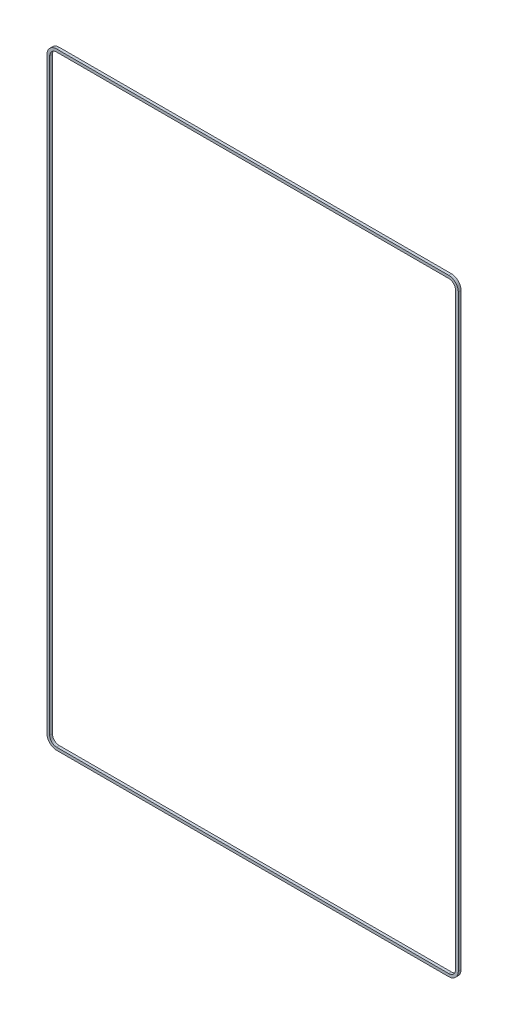
SolidWorks part; units mm, degrees
ref_plane "Front Plane" through (0, 0, 0) normal (0, 0, 1) x (1, 0, 0)
ref_plane "Top Plane" through (0, 0, 0) normal (0, 1, 0) x (1, 0, 0)
ref_plane "Right Plane" through (0, 0, 0) normal (1, 0, 0) x (0, 0, -1)
sketch "Sketch1" plane through (0, 0, 0) normal (0, 0, 1) x (1, 0, 0)
  line L0 (4.318, -2.032) -> (258.318, -2.032) construction
  line L1 (4.318, 0) -> (258.318, 0) construction
  line L2 (0, 4.318) -> (0, 385.318) construction
  line L3 (4.318, 389.636) -> (258.318, 389.636) construction
  line L4 (262.636, 4.318) -> (262.636, 385.318) construction
  line L5 (264.668, 4.318) -> (264.668, 385.318) construction
  line L6 (4.318, 391.668) -> (258.318, 391.668) construction
  line L7 (-2.032, 4.318) -> (-2.032, 385.318) construction
  line L8 (-0.127, 4.318) -> (-0.127, 385.318)
  line L9 (4.318, 389.763) -> (258.318, 389.763)
  line L10 (262.763, 4.318) -> (262.763, 385.318)
  line L11 (4.318, -0.127) -> (258.318, -0.127)
  line L12 (-1.905, 4.318) -> (-1.905, 385.318)
  line L13 (4.318, 391.541) -> (258.318, 391.541)
  line L14 (264.541, 4.318) -> (264.541, 385.318)
  line L15 (4.318, -1.905) -> (258.318, -1.905)
  arc A0 (4.318, 0) -> (0, 4.318) centre (4.318, 4.318) cw construction
  arc A1 (258.318, 0) -> (262.636, 4.318) centre (258.318, 4.318) ccw construction
  arc A2 (258.318, 389.636) -> (262.636, 385.318) centre (258.318, 385.318) cw construction
  arc A3 (0, 385.318) -> (4.318, 389.636) centre (4.318, 385.318) cw construction
  arc A4 (258.318, -2.032) -> (264.668, 4.318) centre (258.318, 4.318) ccw construction
  arc A5 (258.318, 391.668) -> (264.668, 385.318) centre (258.318, 385.318) cw construction
  arc A6 (-2.032, 385.318) -> (4.318, 391.668) centre (4.318, 385.318) cw construction
  arc A7 (4.318, -2.032) -> (-2.032, 4.318) centre (4.318, 4.318) cw construction
  arc A8 (-0.127, 385.318) -> (4.318, 389.763) centre (4.318, 385.318) cw
  arc A9 (258.318, 389.763) -> (262.763, 385.318) centre (258.318, 385.318) cw
  arc A10 (258.318, -0.127) -> (262.763, 4.318) centre (258.318, 4.318) ccw
  arc A11 (4.318, -0.127) -> (-0.127, 4.318) centre (4.318, 4.318) cw
  arc A12 (-1.905, 385.318) -> (4.318, 391.541) centre (4.318, 385.318) cw
  arc A13 (258.318, 391.541) -> (264.541, 385.318) centre (258.318, 385.318) cw
  arc A14 (258.318, -1.905) -> (264.541, 4.318) centre (258.318, 4.318) ccw
  arc A15 (4.318, -1.905) -> (-1.905, 4.318) centre (4.318, 4.318) cw
  point P7 (0, 0)
  point P10 (262.636, 0)
  point P13 (262.636, 389.636)
  point P16 (0, 389.636)
  dimension "D3" = 4.318
  dimension "D1" = 389.636
  dimension "D2" = 262.636
  dimension "D4" = 2.032
  dimension "D5" = 0.127
  dimension "D6" = 1.778
extrude "Boss-Extrude1" add sketch "Sketch1" along normal blind 1.778 contours A15 L15 A14 L14 A13 L13 A12 L12 L11 A11 L8 A8 L9 A9 L10 A10
